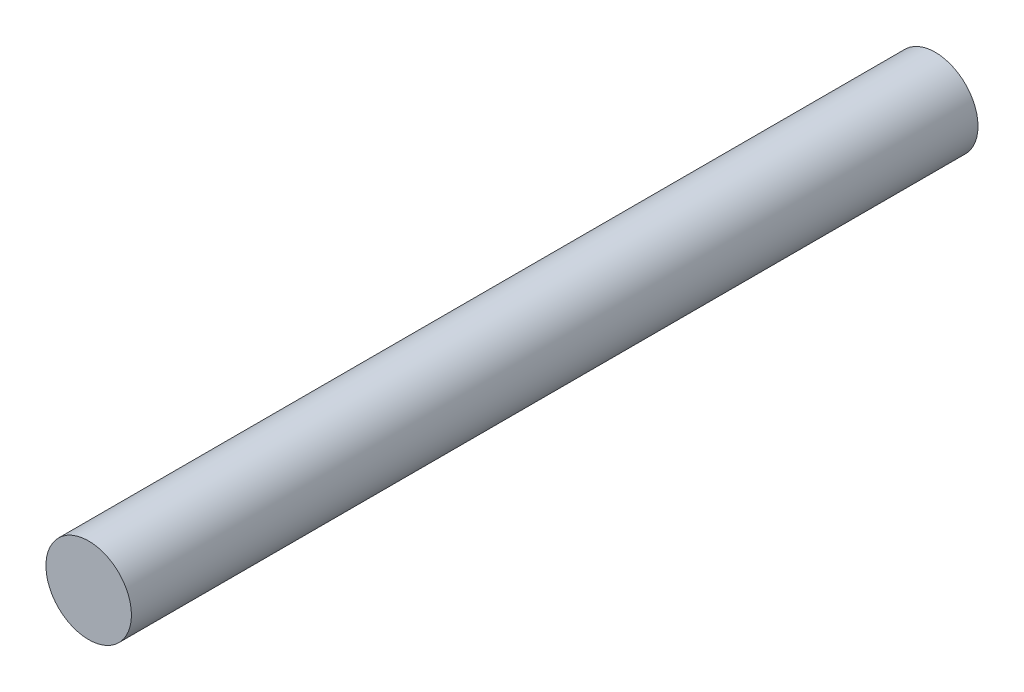
SolidWorks part; units mm, degrees
ref_plane "Front Plane" through (0, 0, 0) normal (1, 0, 0) x (0, 1, 0)
ref_plane "Top Plane" through (0, 0, 0) normal (0, 0, 1) x (0, 1, 0)
ref_plane "Right Plane" through (0, 0, 0) normal (0, 1, 0) x (-1, 0, 0)
sketch "Sketch1" plane through (0, 0, 0) normal (0, 0, 1) x (0, 1, 0)
  circle A0 centre (0, 0) radius 5
  dimension "D1" = 10
extrude "Boss-Extrude1" add sketch "Sketch1" along normal blind 99
